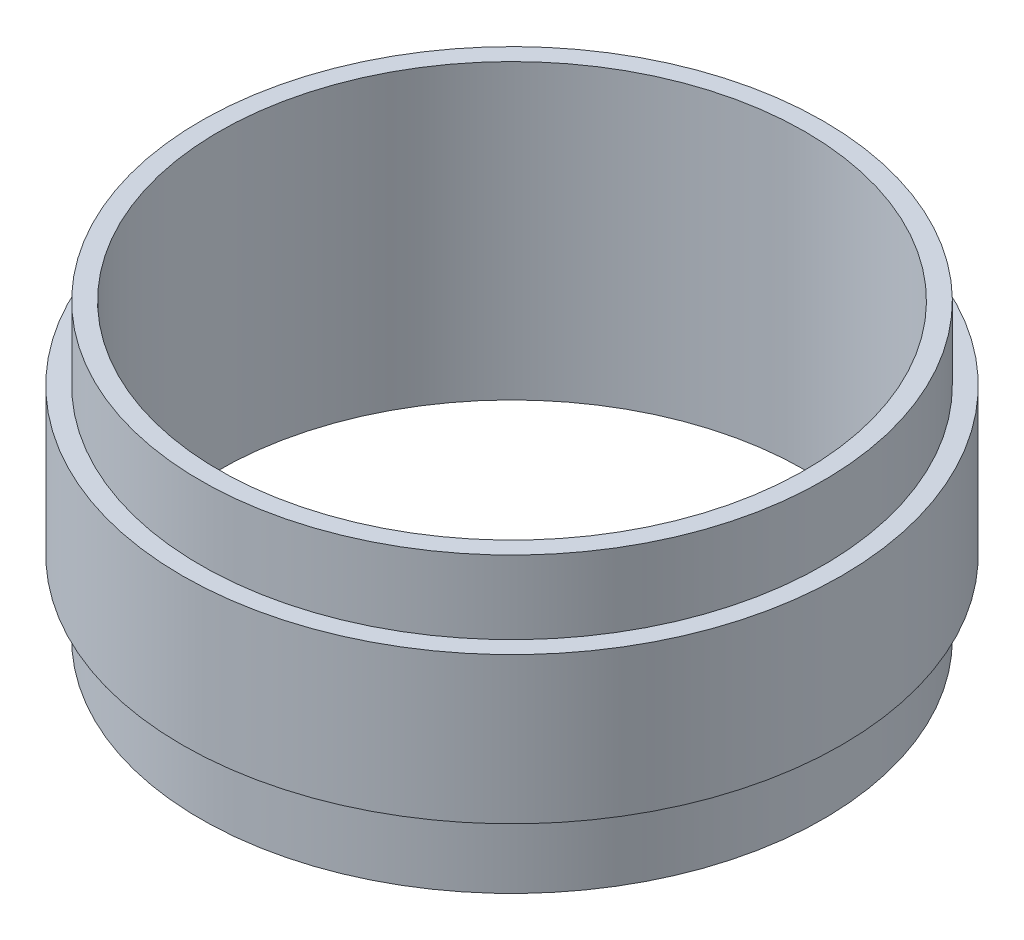
SolidWorks part; units mm, degrees
ref_plane "Front Plane" through (0, 0, 0) normal (0, 0, 1) x (1, 0, 0)
ref_plane "Top Plane" through (0, 0, 0) normal (0, 1, 0) x (1, 0, 0)
ref_plane "Right Plane" through (0, 0, 0) normal (1, 0, 0) x (0, 0, -1)
sketch "Reconstructed nominal axial profile" plane through (0, 0, 0) normal (0, 0, 1) x (1, 0, 0)
  line L0 (0, -500) -> (0, 50) construction
  line L1 (8, -80) -> (8, -72)
  line L2 (8, -72) -> (8.5, -72)
  line L3 (8.5, -72) -> (8.5, -74)
  line L4 (8.5, -74) -> (9, -74)
  line L5 (9, -74) -> (9, -78)
  line L6 (9, -78) -> (8.5, -78)
  line L7 (8.5, -78) -> (8.5, -80)
  line L8 (8.5, -80) -> (8, -80)
revolve "Native revolved geometry" add sketch "Reconstructed nominal axial profile" angle 360 about L0
